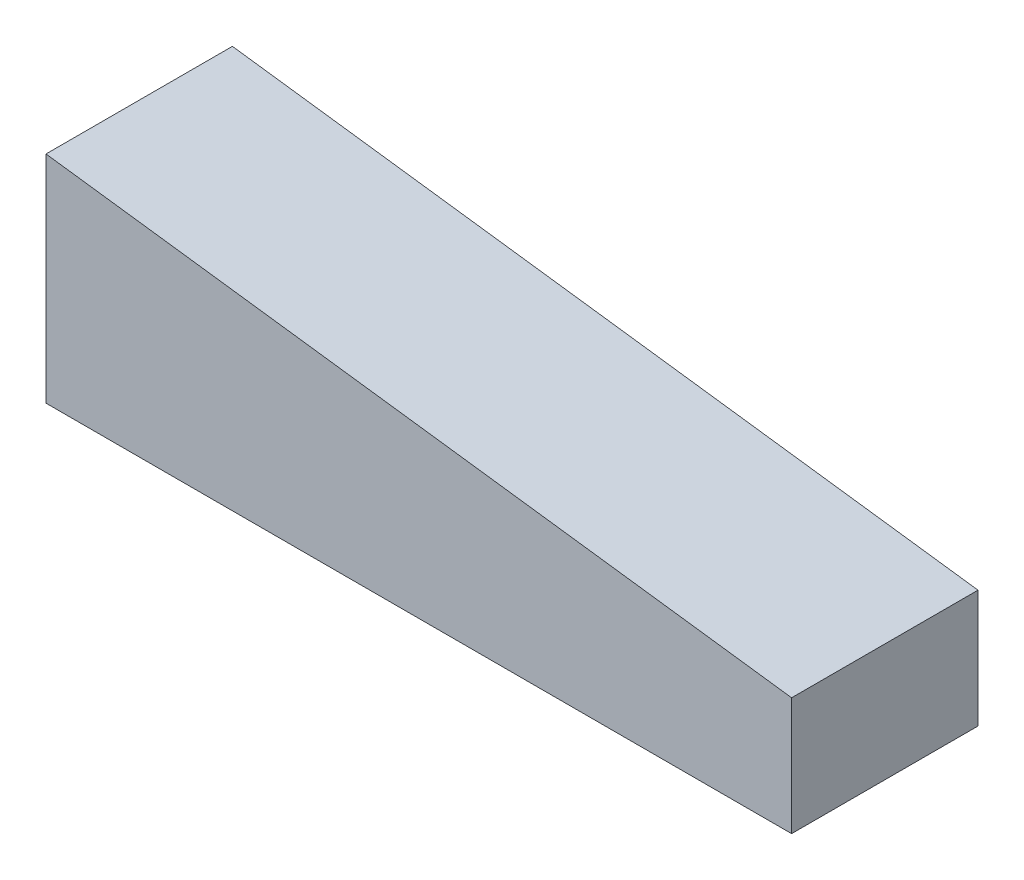
SolidWorks part; units mm, degrees
ref_plane "Front" through (0, 0, 0) normal (0, 0, 1) x (1, 0, 0)
ref_plane "Top" through (0, 0, 0) normal (0, 1, 0) x (1, 0, 0)
ref_plane "Right" through (0, 0, 0) normal (1, 0, 0) x (0, 0, -1)
sketch "Sketch1" plane through (0, 0, 0) normal (0, 0, 1) x (1, 0, 0)
  line L0 (0, 0) -> (0, 14.7064)
  line L1 (0, 14.7064) -> (50.8, 8.0184)
  line L2 (50.8, 8.0184) -> (50.8, 0)
  line L3 (50.8, 0) -> (0, 0)
  line L4 (15.24, 12.7) -> (15.24, 0) construction
  dimension "D1" = 50.8
  dimension "D2" = 12.7
  dimension "D3" = 7.5
  dimension "D4" = 15.24
extrude "Boss-Extrude1" add sketch "Sketch1" along normal mid plane 12.7
